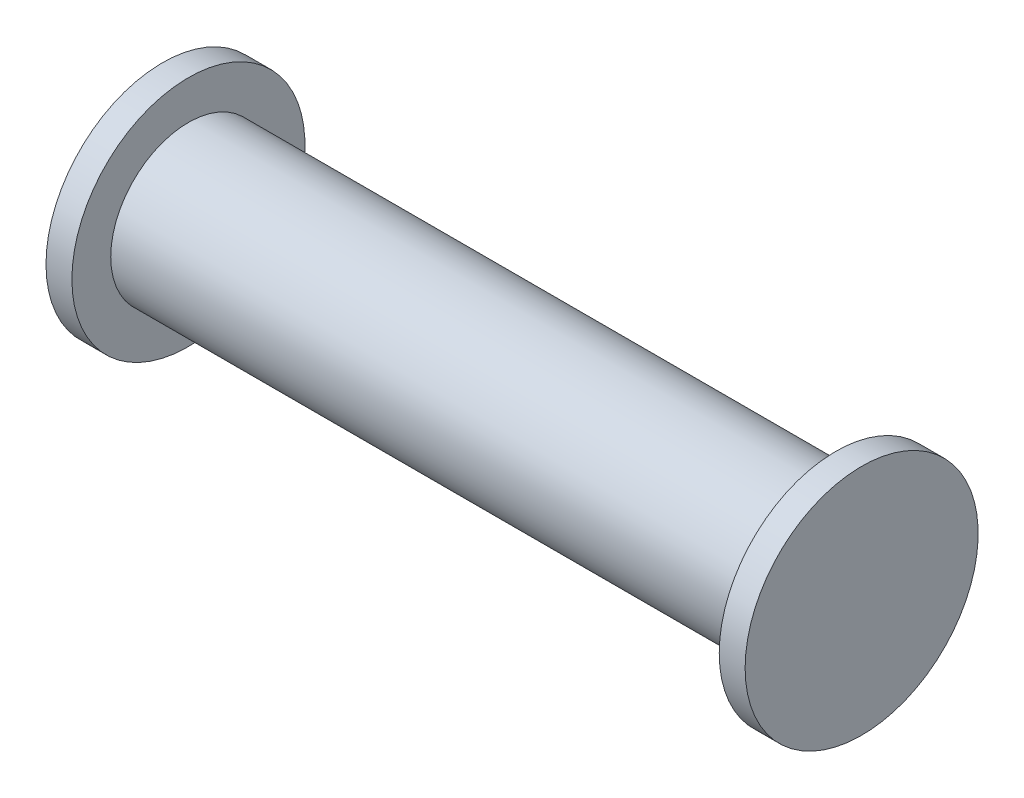
SolidWorks part; units mm, degrees
ref_plane "Front Plane" through (0, 0, 0) normal (0, 0, 1) x (1, 0, 0)
ref_plane "Top Plane" through (0, 0, 0) normal (0, 1, 0) x (1, 0, 0)
ref_plane "Right Plane" through (0, 0, 0) normal (1, 0, 0) x (0, 0, -1)
sketch "Sketch1" plane through (0, 0, 0) normal (0, 0, 1) x (1, 0, 0)
  line L1 (0, 0) -> (42.8625, 0)
  line L2 (0, 0) -> (0, 4.7625)
  line L3 (0, 4.7625) -> (42.8625, 4.7625)
  line L4 (42.8625, 0) -> (42.8625, 4.7625)
  line L5 (0, 4.7625) -> (1.5875, 4.7625)
  line L6 (0, 4.7625) -> (0, 7.1438)
  line L7 (0, 7.1438) -> (1.5875, 7.1438)
  line L8 (1.5875, 4.7625) -> (1.5875, 7.1438)
  line L9 (42.8625, 4.7625) -> (41.275, 4.7625)
  line L10 (42.8625, 4.7625) -> (42.8625, 7.1438)
  line L11 (42.8625, 7.1438) -> (41.275, 7.1438)
  line L12 (41.275, 4.7625) -> (41.275, 7.1438)
  dimension "D1" = 42.8625
  dimension "D2" = 4.7625
  dimension "D3" = 2.3813
  dimension "D4" = 1.5875
revolve "Revolve1" add sketch "Sketch1" angle 360 about L1
